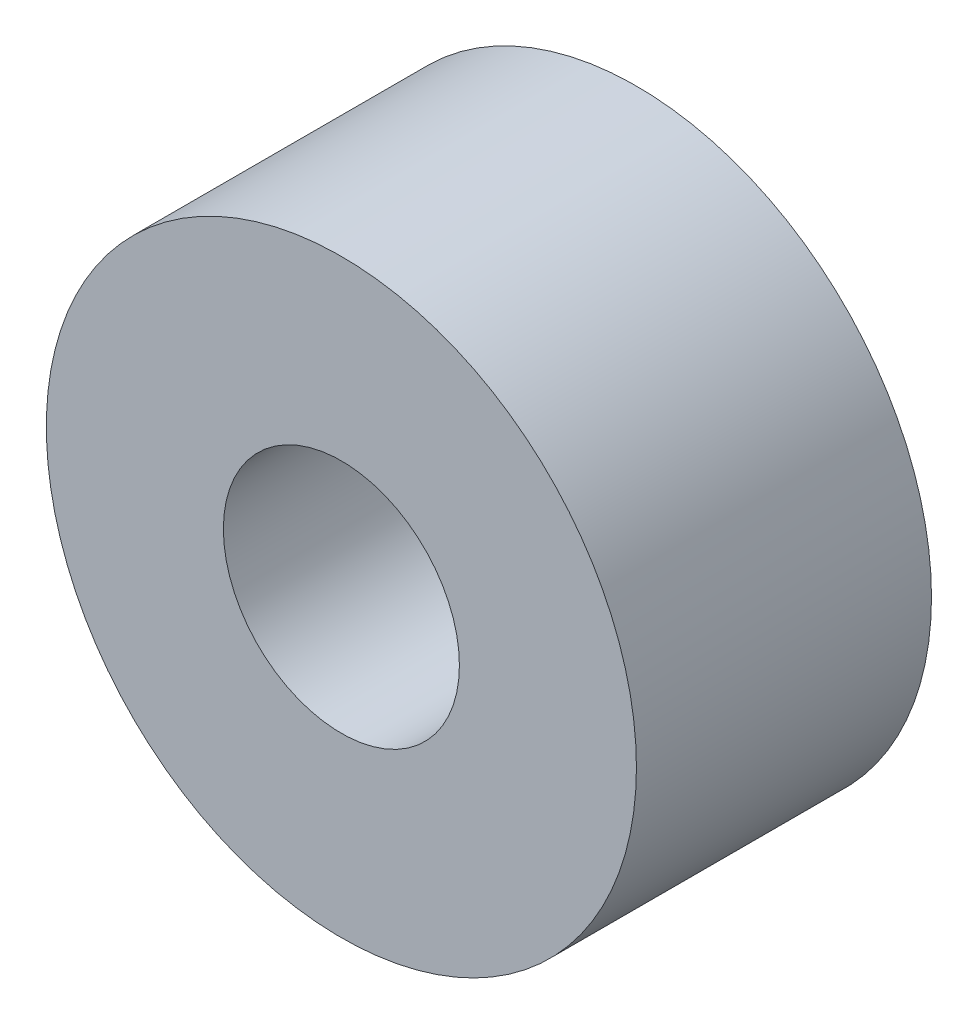
SolidWorks part; units mm, degrees
ref_plane "Alzado" through (0, 0, 0) normal (0, 0, 1) x (1, 0, 0)
ref_plane "Planta" through (0, 0, 0) normal (0, 1, 0) x (1, 0, 0)
ref_plane "Vista lateral" through (0, 0, 0) normal (1, 0, 0) x (0, 0, -1)
sketch "Croquis1" plane through (0, 0, 0) normal (0, 0, 1) x (1, 0, 0)
  circle A0 centre (0, 0) radius 4
  circle A1 centre (0, 0) radius 1.6
  dimension "D1" = 8
  dimension "D2" = 3.2
extrude "Saliente-Extruir1" add sketch "Croquis1" along normal blind 4
